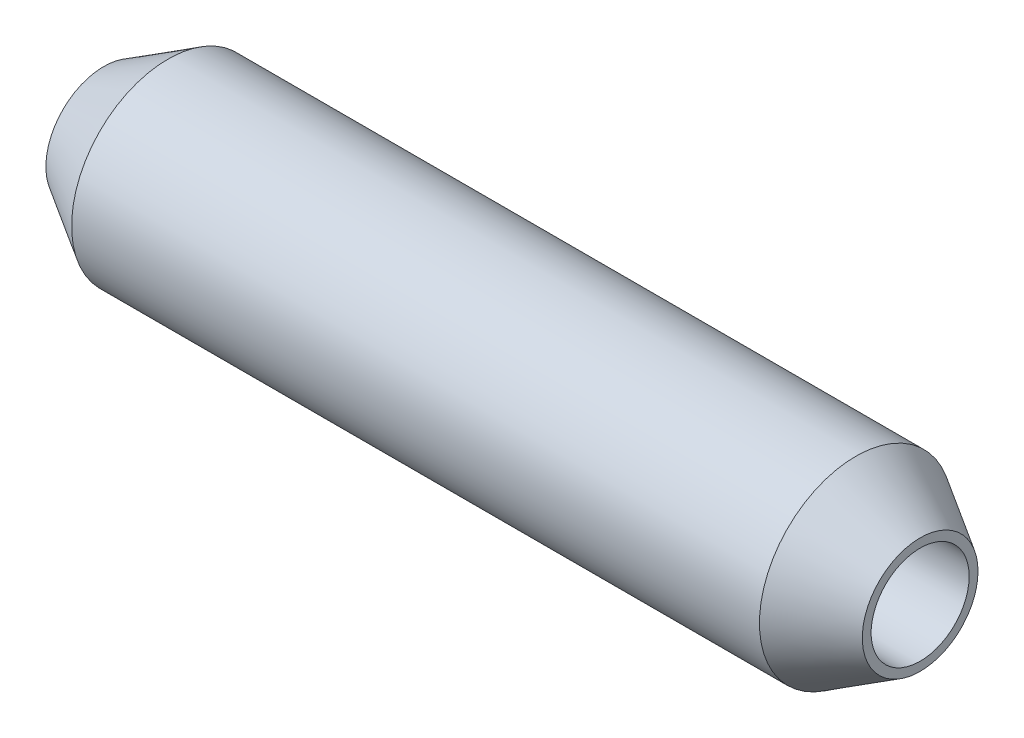
SolidWorks part; units mm, degrees
ref_plane "Front Plane" through (0, 0, 0) normal (0, 0, 1) x (1, 0, 0)
ref_plane "Top Plane" through (0, 0, 0) normal (0, 1, 0) x (1, 0, 0)
ref_plane "Right Plane" through (0, 0, 0) normal (1, 0, 0) x (0, 0, -1)
sketch "Sketch1" plane through (0, 0, 0) normal (1, 0, 0) x (0, 0, -1)
  circle A0 centre (0, 0) radius 3
  circle A1 centre (0, 0) radius 1.525
  dimension "D1" = 6
  dimension "D2" = 3.05
extrude "Boss-Extrude1" add sketch "Sketch1" along normal blind 25.4 contours A0
chamfer "Chamfer1" distance 2 distance2 1.2 2 edges at (0, 0, -3) (25.4, 0, -3)
